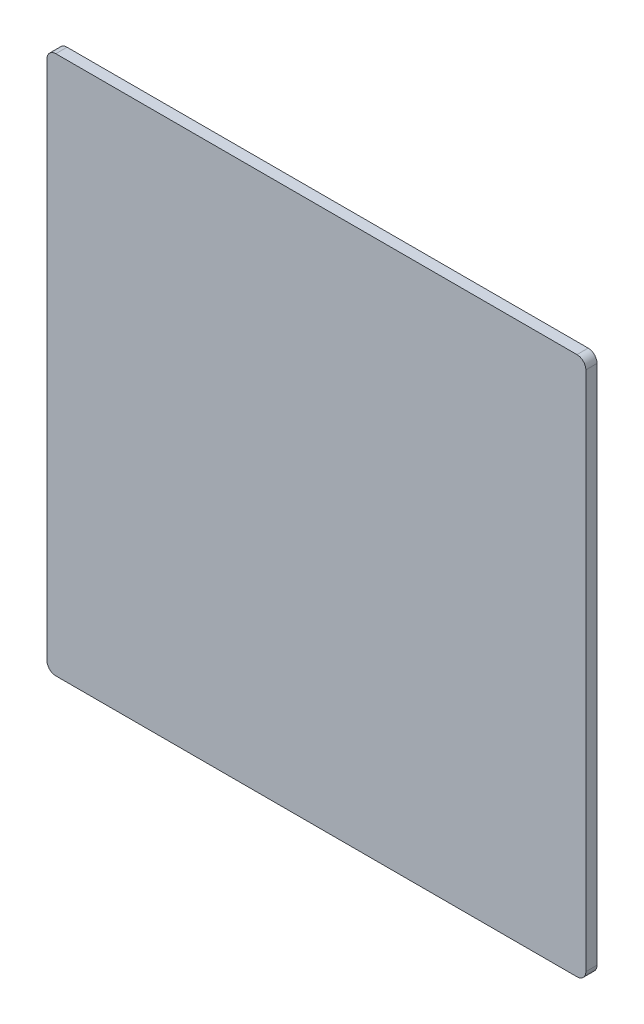
SolidWorks part; units mm, degrees
ref_plane "Front Plane" through (0, 0, 0) normal (0, 0, 1) x (1, 0, 0)
ref_plane "Top Plane" through (0, 0, 0) normal (0, 1, 0) x (1, 0, 0)
ref_plane "Right Plane" through (0, 0, 0) normal (1, 0, 0) x (0, 0, -1)
sketch "Sketch1" plane through (0, 0, 0) normal (0, 0, 1) x (1, 0, 0)
  line L1 (-438.398, 137.4676) -> (171.202, 137.4676)
  line L2 (-438.398, 137.4676) -> (-438.398, -472.1324)
  line L3 (-438.398, -472.1324) -> (171.202, -472.1324)
  line L4 (171.202, 137.4676) -> (171.202, -472.1324)
  dimension "D1" = 609.6
  dimension "D2" = 609.6
  dimension "D3" = 171.202
  dimension "D4" = 137.4676
extrude "Boss-Extrude1" add sketch "Sketch1" along normal blind 12.7 contours L1 L4 L3 L2
fillet "Fillet1" radius 10 4 edges at (171.202, -472.1324, 6.35) (-438.398, -472.1324, 6.35) (-438.398, 137.4676, 6.35) (171.202, 137.4676, 6.35)
